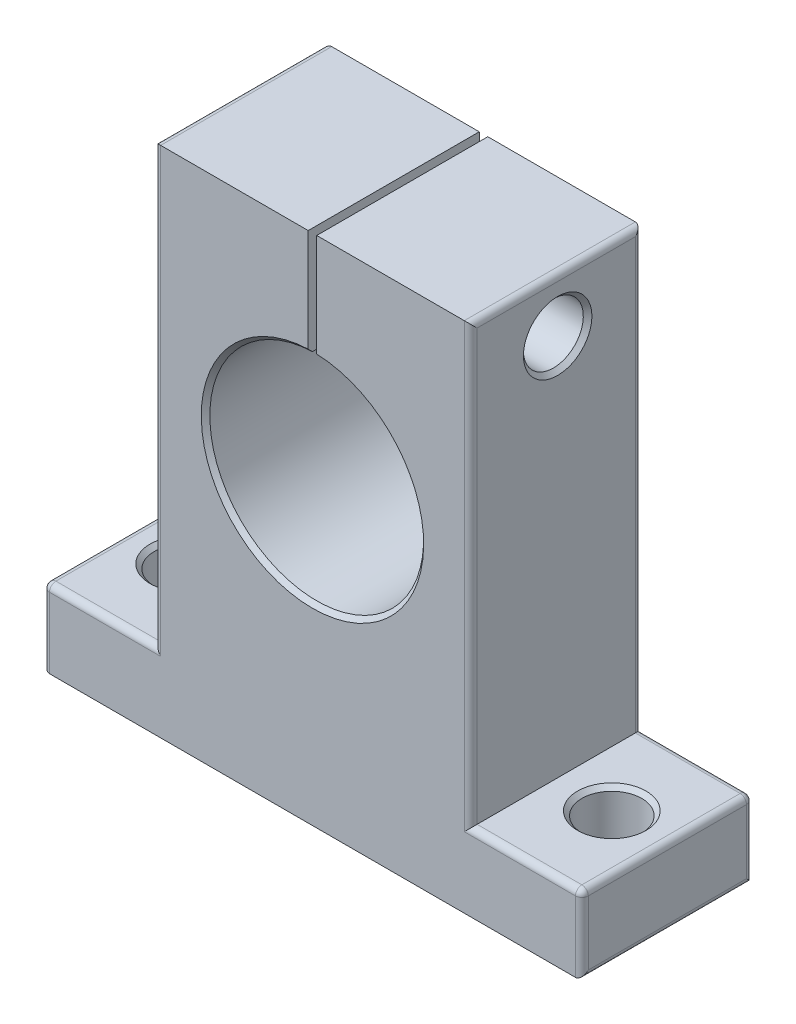
SolidWorks part; units mm, degrees
material "1060 Alloy"
ref_plane "Front Plane" through (0, 0, 0) normal (0, 0, 1) x (1, 0, 0)
ref_plane "Top Plane" through (0, 0, 0) normal (0, 1, 0) x (1, 0, 0)
ref_plane "Right Plane" through (0, 0, 0) normal (1, 0, 0) x (0, 0, -1)
sketch "Sketch1" plane through (0, 0, 0) normal (0, 0, 1) x (1, 0, 0)
  line L0 (0, 0) -> (-50000, 0) construction
  line L1 (0, 0) -> (0, 50000) construction
  line L2 (-63, -9) -> (-63, 9)
  line L3 (-63, 9) -> (-37, 9)
  line L4 (-37, 9) -> (-37, 111)
  line L5 (-37, 111) -> (-1, 111)
  line L6 (37, 111) -> (37, 9)
  line L7 (37, 9) -> (63, 9)
  line L8 (63, 9) -> (63, -9)
  line L9 (63, -9) -> (-63, -9)
  line L10 (50, -3) -> (50, 3) construction
  line L11 (-50, -3) -> (-50, 3) construction
  line L12 (-1, 111) -> (-1, 85.98)
  line L13 (1, 111) -> (1, 85.98)
  line L14 (1, 111) -> (37, 111)
  arc A0 (-1, 85.98) -> (1, 85.98) centre (0, 61) ccw
  point P8 (-63, 0)
  point P15 (0, -9)
  point P21 (50, 0)
  dimension "Shaft Diameter" = 50
  dimension "W" = 126
  dimension "P" = 74
  dimension "F" = 120
  dimension "G" = 18
  dimension "B" = 100
  dimension "D1" = 2
  dimension "h" = 70
extrude "Boss-Extrude1" add sketch "Sketch1" along normal mid plane 40
sketch "Sketch2" plane through (0, 9, 0) normal (0, 1, 0) x (1, 0, 0)
  line L0 (0, 0) -> (50000, 0) construction
  line L1 (0.3141, 0) -> (-49999.6859, 0) construction
  line L2 (0, 2.4842) -> (0, 50002.4842) construction
  circle A0 centre (50, 0) radius 7
  circle A1 centre (-50, 0) radius 7
  dimension "B" = 100
  dimension "S" = 14
extrude "Cut-Extrude1" cut sketch "Sketch2" against normal through all
sketch "Sketch5" plane through (-1, 0, 0) normal (1, 0, 0) x (0, 0, -1)
  line L0 (-20, 98.49) -> (20, 98.49) construction
  line L1 (20, 85.98) -> (20, 111) construction
  line L2 (0, 111) -> (0, 85.98) construction
  line L3 (-20, 111) -> (20, 111) construction
  line L4 (-20, 85.98) -> (20, 85.98) construction
  line L5 (-20, 85.98) -> (-20, 111) construction
  circle A0 centre (0.3307, 98.49) radius 7
  dimension "Clamping bold" = 14
extrude "Cut-Extrude2" cut sketch "Sketch5" against normal through all both and the other way through all
chamfer "Chamfer2" distance 1 angle 45 6 edges at (0, 36, -20) (0, 36, 20) (-37, 98.49, -7.3307) (-43, 9, 0) (37, 98.49, 6.6693) (43, 9, 0)
fillet "Fillet2" radius 1.5 18 edges at (63, -9, 0) (63, 0, 20) (63, 9, 0) (63, 0, -20) (-63, 9, 0) (-63, 0, 20) (-63, -9, 0) (-63, 0, -20) (-50, 9, -20) (-50, 9, 20) (-37, 60, 20) (-37, 111, 0) (-37, 60, -20) (37, 60, -20) (37, 60, 20) (50, 9, 20) (50, 9, -20) (37, 111, 0)
equation "\"W\"= \"W@Sketch1\"'Width"
equation "\"B\"= \"B@Sketch1\"'between hold"
equation "\"F\"= \"F@Sketch1\"'Hight"
equation "\"P\"= \"P@Sketch1\""
equation "\"G\"= \"G@Sketch1\""
equation "\"Shaft diameter\"= \"Shaft Diameter@Sketch1\""
equation "\"S\"= \"S@Sketch2\"'M10"
equation "\"Clamping bold\"= \"Clamping bold@Sketch5\"'M8"
equation "\"h\"= \"h@Sketch1\""
